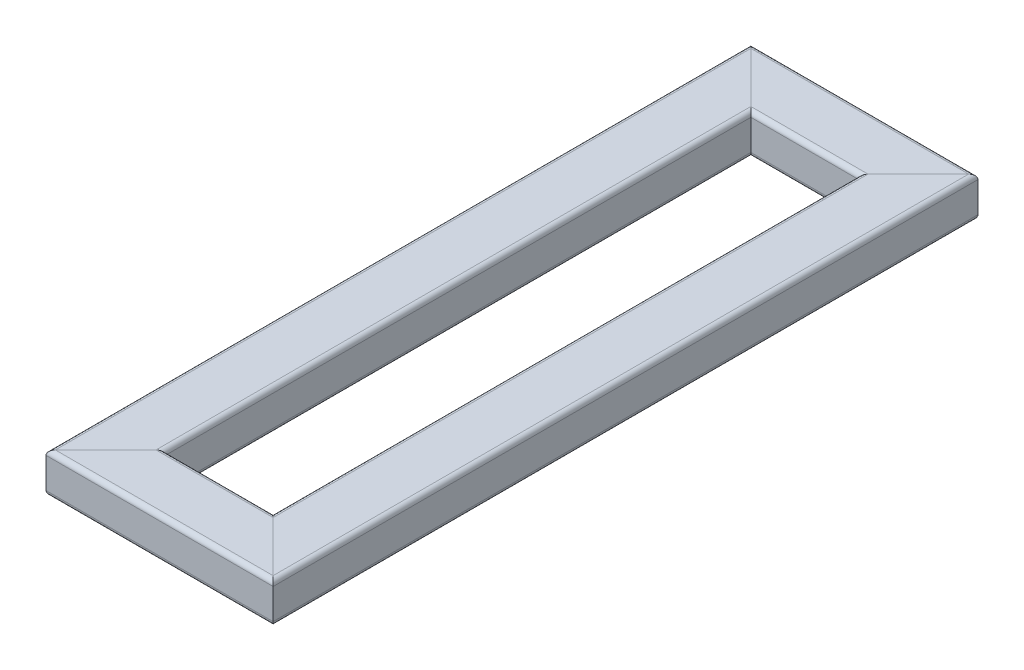
SolidWorks part; units mm, degrees
material "ASTM A36 Acero"
ref_plane "Alzado" through (0, 0, 0) normal (0, 0, 1) x (1, 0, 0)
ref_plane "Planta" through (0, 0, 0) normal (0, 1, 0) x (1, 0, 0)
ref_plane "Vista lateral" through (0, 0, 0) normal (1, 0, 0) x (0, 0, -1)
sketch "Croquis1" plane through (0, 0, 0) normal (0, 1, 0) x (1, 0, 0)
  line L1 (-145, 450) -> (145, 450)
  line L2 (-145, 450) -> (-145, -450)
  line L3 (-145, -450) -> (145, -450)
  line L4 (145, 450) -> (145, -450)
  line L5 (-145, 450) -> (145, -450) construction
  line L6 (-145, -450) -> (145, 450) construction
  point P0 (0, 0)
  dimension "D1" = 900
  dimension "D2" = 290
other "Tubo rectangular 3 X 2 X 0.25(1)"
ref_plane "Plano1" through (-106.9, 25.4, -450) normal (0, 0, 1) x (1, 0, 0)
sketch "Sketch1" plane through (-106.9, 25.4, -450) normal (0, 0, 1) x (1, 0, 0)
  line L0 (-32.1, -22.4) -> (32.1, -22.4)
  line L1 (-35.1, -19.4) -> (-35.1, 19.4)
  line L2 (32.1, 22.4) -> (-32.1, 22.4)
  line L3 (35.1, 19.4) -> (35.1, -19.4)
  line L4 (-32.1, -25.4) -> (32.1, -25.4)
  line L5 (-38.1, -19.4) -> (-38.1, 19.4)
  line L6 (32.1, 25.4) -> (-32.1, 25.4)
  line L7 (38.1, 19.4) -> (38.1, -19.4)
  line L8 (0, 0) -> (38.1, 0) construction
  line L9 (0, 0) -> (0, 25.4) construction
  arc A0 (38.1, 19.4) -> (32.1, 25.4) centre (32.1, 19.4) ccw
  arc A1 (32.1, -25.4) -> (38.1, -19.4) centre (32.1, -19.4) ccw
  arc A2 (-38.1, -19.4) -> (-32.1, -25.4) centre (-32.1, -19.4) ccw
  arc A3 (-32.1, 25.4) -> (-38.1, 19.4) centre (-32.1, 19.4) ccw
  arc A4 (-32.1, 22.4) -> (-35.1, 19.4) centre (-32.1, 19.4) ccw
  arc A5 (35.1, 19.4) -> (32.1, 22.4) centre (32.1, 19.4) ccw
  arc A6 (32.1, -22.4) -> (35.1, -19.4) centre (32.1, -19.4) ccw
  arc A7 (-35.1, -19.4) -> (-32.1, -22.4) centre (-32.1, -19.4) ccw
  point P3 (0, -25.4)
  point P4 (-38.1, 0)
  point P5 (0, 0)
  point P6 (38.1, -25.4)
  point P7 (-38.1, -25.4)
  point P8 (-38.1, 25.4)
  point P33 (0, 0)
  point P35 (38.1, 25.4)
  point P36 (38.1, 0)
  point P37 (0, 25.4)
  dimension "D1" = 6
  dimension "Thickness" = 3
  dimension "V_leg" = 50.8
  dimension "H_leg" = 76.2
